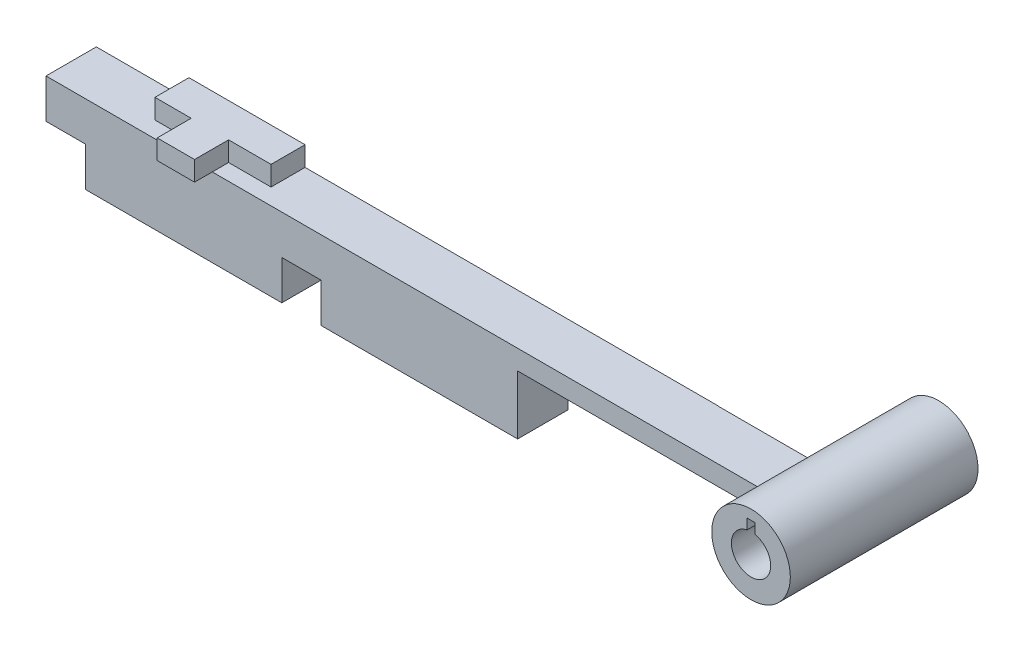
SolidWorks part; units mm, degrees
ref_plane "Front Plane" through (0, 0, 0) normal (0, 0, 1) x (1, 0, 0)
ref_plane "Top Plane" through (0, 0, 0) normal (0, 1, 0) x (1, 0, 0)
ref_plane "Right Plane" through (0, 0, 0) normal (1, 0, 0) x (0, 0, -1)
sketch "Sketch1" plane through (0, 0, 0) normal (0, 1, 0) x (1, 0, 0)
  line L1 (0, 0) -> (14, 0)
  line L2 (0, 0) -> (0, 10)
  line L3 (0, 10) -> (14, 10)
  line L4 (14, 0) -> (14, 10)
extrude "Boss-Extrude1" add sketch "Sketch1" along normal blind 5
sketch "Sketch2" plane through (0, 5, 0) normal (0, 1, 0) x (1, 0, 0)
  line L0 (7, 10) -> (7, 0)
  line L1 (14, 10) -> (0, 10) construction
  line L2 (0, 0) -> (14, 0) construction
  line L3 (7, 5) -> (9, 5)
  line L4 (7, 5) -> (5, 5)
  line L5 (5, 5) -> (5, 5.9618)
  line L6 (5, 5.9618) -> (5, 3.9618)
  line L7 (5, 3.9618) -> (9, 3.9618)
  line L8 (9, 3.9618) -> (9, 5.9618)
  line L9 (9, 5.9618) -> (5, 5.9618)
  line L10 (7, 5.9618) -> (6, 5.9618)
  line L11 (6, 5.9618) -> (6, 7.6627)
  line L12 (6, 7.6627) -> (8.1375, 7.6627)
  line L13 (8.1375, 5.9618) -> (8.1375, 7.6627)
  line L14 (8.1375, 3.9618) -> (8.1375, 1.9618)
  line L15 (8.1375, 1.9618) -> (6, 1.9618)
  line L16 (6, 1.9618) -> (6, 3.9618)
extrude "Boss-Extrude2" add sketch "Sketch2" along normal blind 3 contours L9 L13 L12 L0 | L12 L11 L9 L0 | L0 L9 L5 L4 | L6 L7 L0 L4 | L8 L9 L0 L3 | L7 L8 L3 L0 | L16 L15 L0 L7 | L15 L14 L7 L0
sketch "Sketch3" plane through (0, 0, 0) normal (0, -1, 0) x (1, 0, 0)
  line L1 (0, -10) -> (14, -10)
  line L2 (0, -10) -> (0, 0)
  line L3 (0, 0) -> (14, 0)
  line L4 (14, -10) -> (14, 0)
extrude "Cut-Extrude1" cut sketch "Sketch3" against normal blind 3
sketch "Sketch5" plane through (0, 3, 0) normal (0, -1, 0) x (1, 0, 0)
  line L0 (7, 0) -> (2, 0)
  line L1 (14, 0) -> (0, 0) construction
  line L2 (2, 0) -> (12, 0)
  line L3 (12, 0) -> (12, -3)
  line L4 (12, -3) -> (2, -3)
  line L5 (2, -3) -> (2, 0)
  line M8 (14, 0) -> (0, 0)
extrude "Boss-Extrude3" add sketch "Sketch5" along normal blind 9 contours L5 L4 L3 M8
sketch "Sketch6" plane through (14, 0, 0) normal (1, 0, 0) x (0, 0, -1)
  line L1 (0, 3) -> (10, 3)
  line L2 (0, 3) -> (0, 5)
  line L3 (0, 5) -> (10, 5)
  line L4 (10, 3) -> (10, 5)
extrude "Boss-Extrude4" add sketch "Sketch6" along normal blind 43
sketch "Sketch7" plane through (0, 0, 0) normal (0, 0, 1) x (1, 0, 0)
  line L0 (57, 5) -> (57, 3) construction
  circle A0 centre (57, 4) radius 5
extrude "Boss-Extrude5" add sketch "Sketch7" against normal blind 14 and the other way blind 23
sketch "Sketch8" plane through (0, 3, 0) normal (0, -1, 0) x (-1, 0, 0)
  line L0 (-12, 0) -> (-14, 0)
  line L1 (-52.101, 0) -> (-12, 0) construction
  line L2 (-14, 0) -> (-14, 3)
  line L3 (-14, 3) -> (-24, 3)
  line L4 (-24, 3) -> (-24, 0)
  line L5 (-24, 0) -> (-14, 0)
  line M6 (-52.101, 0) -> (-12, 0)
extrude "Boss-Extrude6" add sketch "Sketch8" along normal blind 9 contours L3 L4 L2 M6
sketch "Sketch9" plane through (0, 5, 0) normal (0, 1, 0) x (1, 0, 0)
  line L0 (9, 4.9618) -> (19, 4.9618)
  line L1 (9, 3.9618) -> (9, 5.9618) construction
  line L2 (19, 4.9618) -> (8.1375, 7.6627)
  line L3 (8.1375, 7.6627) -> (19, 7.6627)
  line L4 (19, 7.6627) -> (21, 7.6627)
  line L5 (19, 7.6627) -> (17.0048, 7.6627)
  line L6 (17.0048, 7.6627) -> (17.0048, 1.6627)
  line L7 (17.0048, 1.6627) -> (21, 1.6627)
  line L8 (21, 1.6627) -> (21, 7.6627)
  line L9 (17.0048, 7.6627) -> (18.0024, 7.6627)
  line L10 (18.0024, 7.6627) -> (18.0024, 1.6627)
  line L11 (18.0024, 1.6627) -> (20, 1.6627)
  line L12 (20, 1.6627) -> (20, 7.6627)
  line L13 (20, 7.6627) -> (20, 4.6627)
  line L14 (20, 4.6627) -> (20, 7.6627)
  line L15 (20, 6.1627) -> (21.5, 6.1627)
  line L16 (21.5, 6.1627) -> (21.5, 3.1627)
  line L17 (21.5, 3.1627) -> (20, 3.1627)
  line L18 (20, 3.1627) -> (15.5, 3.1627)
  line L19 (15.5, 3.1627) -> (15.5, 6.1627)
  line L20 (16, 6.1619) -> (16, 3.1627)
  line L21 (15.5, 6.1627) -> (16, 6.1619)
  line L22 (16, 3.1627) -> (16, 6.1619)
  line L23 (16.1006, 6.1619) -> (17.0048, 6.1619)
  line L24 (16, 6.1619) -> (16.1006, 6.1619)
  line L25 (17.0048, 6.1619) -> (18.0024, 6.1619)
extrude "Boss-Extrude7" add sketch "Sketch9" along normal blind 3 contours L25 L6 L2 L10 | L24 L20 L2 L6 L23 | L2 L20 L0 L6 | L10 L2 L6 L0 | L0 L20 L18 L6 | L18 L10 L0 L6 | L2 L10 L0 | L18 L12 L14 L4 L5 L10 L2 L0 | L17 L8 L15 L12 | L12 L18 L10 L7
sketch "Sketch10" plane through (0, 8, 0) normal (0, 1, 0) x (1, 0, 0)
  line L0 (18.0024, 6.1619) -> (17.0012, 6.1619)
  line L1 (16, 6.1619) -> (18.0024, 6.1619) construction
  line L2 (17.0012, 6.1619) -> (17.0012, 3.1627)
  line L3 (18.0024, 3.1627) -> (16, 3.1627) construction
  line L4 (17.0012, 3.1627) -> (16, 3.1627)
  line L5 (16, 6.1619) -> (16, 3.1627) construction
  line L6 (16, 6.1619) -> (16, 3.1627) construction
  line L7 (16, 3.1627) -> (16, 6.1619)
  line L8 (16, 6.1619) -> (17.0012, 6.1619)
  line M5 (16, 6.1619) -> (16, 3.1627)
  line M6 (16, 3.1627) -> (18.0024, 3.1627)
  line M16 (18.0024, 6.1619) -> (16, 6.1619)
extrude "Cut-Extrude2" cut sketch "Sketch10" against normal blind 3 contours L2 M16 M5 M6
sketch "Sketch11" plane through (0, 0, 23) normal (0, 0, 1) x (1, 0, 0)
  line L0 (52, 4) -> (62, 4)
  line L1 (57, 6) -> (57, 6.7951)
  line L2 (57, 6.7951) -> (57.5, 6.7951)
  line L3 (57.5, 6.7951) -> (57.5, 5.9365)
  line L4 (57, 6.7951) -> (56.5, 6.7951)
  line L5 (56.5, 6.7951) -> (56.5, 5.9365)
  arc A0 (52.101, 5) -> (52.101, 3) centre (57, 4) ccw construction
  circle A1 centre (57, 4) radius 5 construction
  circle A2 centre (57, 4) radius 2
extrude "Cut-Extrude3" cut sketch "Sketch11" against normal blind 43 contours A2 L1 L4 L5 | A2 L3 L2 L1 | L0 A2 | L0 A2
sketch "Sketch12" plane through (0, 8, 0) normal (0, 1, 0) x (1, 0, 0)
  line L1 (6, 1.9618) -> (8.1375, 1.9618)
  line L2 (6, 1.9618) -> (6, 7.6627)
  line L3 (6, 7.6627) -> (8.1375, 7.6627)
  line L4 (8.1375, 1.9618) -> (8.1375, 7.6627)
  line L5 (5, 3.9618) -> (9, 3.9618)
  line L6 (5, 3.9618) -> (5, 5.9618)
  line L7 (5, 5.9618) -> (9, 5.9618)
  line L8 (9, 3.9618) -> (9, 5.9618)
  line L9 (17.0012, 3.1627) -> (21, 3.1627)
  line L10 (17.0012, 3.1627) -> (17.0012, 6.1627)
  line L11 (17.0012, 6.1627) -> (21, 6.1627)
  line L12 (21, 3.1627) -> (21, 6.1627)
  line L13 (18.0024, 1.6627) -> (20, 1.6627)
  line L14 (18.0024, 1.6627) -> (18.0024, 7.6627)
  line L15 (18.0024, 7.6627) -> (20, 7.6627)
  line L16 (20, 1.6627) -> (20, 7.6627)
  line M5 (6, 3.9618) -> (6, 1.9618)
  line M6 (6, 1.9618) -> (8.1375, 1.9618)
  line M7 (8.1375, 1.9618) -> (8.1375, 3.9618)
  line M8 (8.1375, 3.9618) -> (9, 3.9618)
  line M9 (9, 3.9618) -> (9, 5.9618)
  line M10 (9, 5.9618) -> (8.1375, 5.9618)
  line M11 (8.1375, 5.9618) -> (8.1375, 7.6627)
  line M12 (8.1375, 7.6627) -> (6, 7.6627)
  line M13 (6, 7.6627) -> (6, 5.9618)
  line M14 (6, 5.9618) -> (5, 5.9618)
  line M15 (5, 5.9618) -> (5, 3.9618)
  line M16 (5, 3.9618) -> (6, 3.9618)
extrude "Cut-Extrude4" cut sketch "Sketch12" against normal blind 4 contours L5 M5 M6 M7 | L7 L2 L5 L4 | L2 M16 M14 M15 | L7 M13 M11 M12 | L4 M8 M9 M10 | L13 L16 L9 L14 | L9 L16 L11 L14 | L16 L9 L12 L11 | L11 L16 L15 L14 | L9 L14 L11 L10
sketch "Sketch14" plane through (0, 3, 0) normal (0, -1, 0) x (1, 0, 0)
  line L0 (52.101, 0) -> (52.101, -10) construction
  line L1 (0, -10) -> (24, -10)
  line L2 (0, -10) -> (0, -3)
  line L3 (0, -3) -> (24, -3)
  line L4 (24, -10) -> (24, -3)
  line L5 (24, -10) -> (52.101, -10)
  line L6 (24, -10) -> (24, -3)
  line L7 (24, -3) -> (52.101, -3)
  line L8 (52.101, -10) -> (52.101, -3)
  line M2 (24, -3) -> (14, -3)
  line M6 (12, -3) -> (2, -3)
  line M9 (0, 0) -> (0, -10)
  line M10 (0, -10) -> (52.101, -10)
  line M11 (52.101, -10) -> (52.101, 0)
extrude "Cut-Extrude6" cut sketch "Sketch14" against normal blind 4 contours L4 L3 M10 M2 M6 M9 | L7 L4 M10 M11
sketch "Sketch15" plane through (0, 4, 0) normal (0, 1, 0) x (1, 0, 0)
  line L1 (18.0024, 1.6627) -> (20, 1.6627)
  line L2 (18.0024, 1.6627) -> (18.0024, 3)
  line L3 (18.0024, 3) -> (20, 3)
  line L4 (20, 1.6627) -> (20, 3)
  line L5 (6, 1.9618) -> (8.1375, 1.9618)
  line L6 (6, 1.9618) -> (6, 3)
  line L7 (6, 3) -> (8.1375, 3)
  line L8 (8.1375, 1.9618) -> (8.1375, 3)
extrude "Boss-Extrude8" add sketch "Sketch15" along normal blind 1
sketch "Sketch16" plane through (0, 5, 0) normal (0, 1, 0) x (1, 0, 0)
  line L3 (4.7132, 0.8299) -> (10.6225, 0.8299)
  line L4 (4.7132, 0.8299) -> (4.7132, 2.5614)
  line L5 (6.5593, -0.9012) -> (8.4612, -0.9012)
  line L6 (6.5593, -0.9012) -> (6.5593, 4.4069)
  line L7 (6.5593, 4.4069) -> (8.4612, 4.4069)
  line L8 (8.4612, -0.9012) -> (8.4612, 4.4069)
  line L9 (4.7132, 2.5614) -> (10.6225, 2.5614)
  line L10 (10.6225, 0.8299) -> (10.6225, 2.5614)
  line M10 (52.101, 3) -> (0, 3)
  line M12 (0, 0) -> (52.101, 0)
extrude "Boss-Extrude9" add sketch "Sketch16" along normal blind 1 contours L3 L10 L9 L8 | L9 L6 L3 L8 | L8 L7 L6 M10 | L5 L8 L6 M12 | L9 L4 L3 L6 | L8 L3 L6 M12 | L6 L9 L8 M10
sketch "Sketch17" plane through (0, 3, 0) normal (0, -1, 0) x (1, 0, 0)
  line L1 (24, -3) -> (52.101, -3)
  line L2 (24, -3) -> (24, 0)
  line L3 (24, 0) -> (52.101, 0)
  line L4 (52.101, -3) -> (52.101, 0)
extrude "Cut-Extrude7" cut sketch "Sketch17" against normal blind 1
sketch "Sketch18" plane through (0, 0, 23) normal (0, 0, 1) x (1, 0, 0)
  circle A0 centre (57, 4) radius 5
extrude "Cut-Extrude8" cut sketch "Sketch18" against normal blind 7
sketch "Sketch19" plane through (0, 0, -14) normal (0, 0, -1) x (-1, 0, 0)
  circle A0 centre (-57, 4) radius 5
extrude "Cut-Extrude9" cut sketch "Sketch19" against normal blind 8
sketch "Sketch20" plane through (0, 0, 16) normal (0, 0, 1) x (1, 0, 0)
  circle A0 centre (57, 4) radius 5
extrude "Cut-Extrude10" cut sketch "Sketch20" against normal blind 31
sketch "Sketch21" plane through (0, 5, 0) normal (0, 1, 0) x (1, 0, 0)
  line L0 (52.101, 3) -> (8.4612, 3) construction
  line L1 (52.101, 0) -> (34.604, 0)
  line L2 (52.101, 0) -> (52.101, 3)
  line L3 (52.101, 3) -> (34.604, 3)
  line L4 (34.604, 0) -> (34.604, 3)
extrude "Cut-Extrude11" cut sketch "Sketch21" against normal blind 31
sketch "Sketch22" plane through (0, -6, 0) normal (0, -1, 0) x (1, 0, 0)
  line L1 (2, -3) -> (12, -3)
  line L2 (2, -3) -> (2, 0)
  line L3 (2, 0) -> (12, 0)
  line L4 (12, -3) -> (12, 0)
  line L5 (14, -3) -> (24, -3)
  line L6 (14, -3) -> (14, 0)
  line L7 (14, 0) -> (24, 0)
  line L8 (24, -3) -> (24, 0)
extrude "Cut-Extrude12" cut sketch "Sketch22" against normal blind 7
sketch "Sketch23" plane through (0, 6, 0) normal (0, 1, 0) x (1, 0, 0)
  line L1 (6.5593, 4.4069) -> (8.4612, 4.4069)
  line L2 (6.5593, 4.4069) -> (6.5593, 3)
  line L3 (6.5593, 3) -> (8.4612, 3)
  line L4 (8.4612, 4.4069) -> (8.4612, 3)
extrude "Cut-Extrude13" cut sketch "Sketch23" against normal blind 2
sketch "Sketch24" plane through (0, 0, 0) normal (0, 0, 1) x (1, 0, 0)
  line L0 (34.604, 4) -> (34.604, 5) construction
  circle A0 centre (34.604, 4.5) radius 3
extrude "Boss-Extrude10" add sketch "Sketch24" along normal blind 10 and the other way blind 6
sketch "Sketch25" plane through (0, 0, 10) normal (0, 0, 1) x (1, 0, 0)
  line L0 (31.604, 4.5) -> (37.604, 4.5)
  line L1 (34.604, 5.5) -> (34.604, 6)
  line L2 (34.604, 6) -> (34.804, 6)
  line L3 (34.804, 6) -> (34.804, 5.4798)
  line L4 (34.804, 5.4798) -> (34.604, 6)
  line L5 (34.404, 6) -> (34.604, 6)
  line L6 (34.404, 6) -> (34.404, 5.4798)
  arc A0 (31.6459, 5) -> (31.6459, 4) centre (34.604, 4.5) ccw construction
  circle A1 centre (34.604, 4.5) radius 3 construction
  circle A2 centre (34.604, 4.5) radius 1
extrude "Cut-Extrude14" cut sketch "Sketch25" against normal blind 16 contours L0 A2 | L0 A2 | L4 L3 L2 | A2 L4 L1 | A2 L1 L5 L6
sketch "Sketch26" plane through (0, 0, 10) normal (0, 0, 1) x (1, 0, 0)
  circle A0 centre (34.604, 4.5) radius 3
  circle A1 centre (34.604, 4.5) radius 2.5
extrude "Cut-Extrude18" cut sketch "Sketch26" against normal blind 10 contours A1 | A0
sketch "Sketch27" plane through (0, 0, -6) normal (0, 0, -1) x (-1, 0, 0)
  circle A0 centre (-34.604, 4.5) radius 3
  circle A1 centre (-34.604, 4.5) radius 2.5
extrude "Cut-Extrude19" cut sketch "Sketch27" against normal blind 3 contours A0
sketch "Sketch28" plane through (0, 0, 10) normal (0, 0, 1) x (1, 0, 0)
  circle A0 centre (34.604, 4.5) radius 2.5
extrude "Cut-Extrude20" cut sketch "Sketch28" against normal blind 4
sketch "Sketch29" plane through (0, 5, 0) normal (0, 1, 0) x (1, 0, 0)
  line L1 (0, 3) -> (10.6225, 3)
  line L2 (0, 3) -> (0, 2.5614)
  line L3 (0, 2.5614) -> (10.6225, 2.5614)
  line L4 (10.6225, 3) -> (10.6225, 2.5614)
  line L5 (10.6225, 2.5614) -> (31.6459, 2.5614)
  line L6 (10.6225, 2.5614) -> (10.6225, 3)
  line L7 (10.6225, 3) -> (31.6459, 3)
  line L8 (31.6459, 2.5614) -> (31.6459, 3)
  line M5 (4.7132, 2.5614) -> (6.5593, 2.5614)
  line M6 (6.5593, 2.5614) -> (6.5593, 3)
  line M7 (6.5593, 3) -> (0, 3)
  line M8 (0, 3) -> (0, 0)
extrude "Cut-Extrude22" cut sketch "Sketch29" against normal blind 7 and the other way blind 2 contours L3 M8 M5 M6 M7 | L4 L1 L3 M6 | L5 L8 L7 L4
sketch "Sketch30" plane through (0, 0, 6) normal (0, 0, 1) x (1, 0, 0)
  circle A0 centre (34.604, 4.5) radius 3
extrude "Cut-Extrude23" cut sketch "Sketch30" against normal blind 10
sketch "Sketch31" plane through (0, 0, 0) normal (0, 0, 1) x (1, 0, 0)
  line L0 (31.6459, 4) -> (24, 4) construction
  line L1 (28.802, 4) -> (31.2329, 4)
  line L2 (28.802, 4) -> (28.802, 5)
  line L3 (28.802, 5) -> (31.2329, 5)
  line L4 (31.2329, 4) -> (31.2329, 5)
  line L5 (8.4612, 5) -> (31.6459, 5) construction
  line L7 (31.2329, 4) -> (37.4677, 4)
  line L8 (31.2329, 4) -> (31.2329, 5)
  line L9 (31.2329, 5) -> (37.4677, 5)
  line L10 (37.4677, 4) -> (37.4677, 5)
  arc M6 (31.6459, 4) -> (31.6459, 5) centre (34.604, 4.5) cw
extrude "Boss-Extrude11" add sketch "Sketch31" against normal blind 2.55 contours L7 L10 L9 M6
sketch "Sketch32" plane through (0, 0, 0) normal (0, 0, 1) x (1, 0, 0)
  line L0 (24, 4) -> (37.4677, 4)
  line L1 (37.4677, 4) -> (30.7339, 4)
  line L2 (30.7339, 4) -> (34.1008, 4)
  line L3 (34.1008, 4) -> (34.1008, 5)
  line L4 (8.4612, 5) -> (37.4677, 5) construction
  circle A0 centre (34.1008, 4.5) radius 2
  line M3 (37.4677, 5) -> (8.4612, 5)
extrude "Boss-Extrude12" add sketch "Sketch32" along normal blind 7.55 and the other way blind 6 contours A0 M3 | L1 A0 L3 M3 | A0 L2 L3 M3 | L2 A0 L1
sketch "Sketch33" plane through (0, 0, 7.55) normal (0, 0, 1) x (1, 0, 0)
  line L0 (32.1008, 4.5) -> (36.1008, 4.5)
  line L1 (34.1008, 5.5) -> (34.1008, 6)
  line L2 (34.1008, 6) -> (34.3008, 6)
  line L3 (34.3008, 6) -> (34.3008, 5.4798)
  line L4 (34.3008, 5.4798) -> (34.1008, 6)
  line L5 (34.1008, 6) -> (33.9008, 6)
  line L6 (33.9008, 6) -> (33.9008, 5.4798)
  circle A0 centre (34.1008, 4.5) radius 2 construction
  arc A1 (36.0373, 4) -> (36.0373, 5) centre (34.1008, 4.5) ccw construction
  circle A2 centre (34.1008, 4.5) radius 1
extrude "Cut-Extrude24" cut sketch "Sketch33" against normal blind 13.55 contours L0 A2 | L0 A2 | A2 L4 L1 | L4 L3 L2 | A2 L1 L5 L6
sketch "Sketch34" plane through (0, 0, 0) normal (0, 0, 1) x (1, 0, 0)
  line L0 (37.4677, 4) -> (39.9677, 4)
  line L1 (36.0373, 4) -> (37.4677, 4)
  line L2 (36.0373, 4) -> (36.0373, 5)
  line L3 (36.0373, 5) -> (37.4677, 5)
  line L4 (37.4677, 4) -> (37.4677, 5)
  line L5 (37.4677, 5) -> (39.9677, 5)
  line L6 (39.9677, 5) -> (39.9677, 4)
  line L7 (39.017, 5.956) -> (39.9677, 5)
  line L8 (39.9677, 5) -> (41.8177, 6.8398)
  line L9 (41.8177, 6.8398) -> (39.017, 5.956)
  line L10 (40.8927, 7.7698) -> (39.017, 5.956)
  line L11 (40.8927, 7.7698) -> (41.8177, 6.8398)
  arc A1 (37.4677, 4) -> (39.9677, 5) centre (37.3034, 8.0358) ccw
  arc A2 (37.4677, 5) -> (39.017, 5.956) centre (36.0168, 9.0846) ccw
  line M10 (37.4677, 4) -> (37.4677, 5)
extrude "Boss-Extrude13" add sketch "Sketch34" against normal blind 2.55 contours A1 L5 M10 | A2 L5 L7 | L8 L9 L7 | L11 L10 L9
sketch "Sketch35" plane through (0, 0, 0) normal (0, 0, 1) x (1, 0, 0)
  line L0 (40.8927, 7.7698) -> (41.8177, 6.8398) construction
  circle A0 centre (41.3552, 7.3048) radius 2
extrude "Boss-Extrude14" add sketch "Sketch35" along normal blind 6.55 and the other way blind 4
sketch "Sketch36" plane through (0, 0, 7.55) normal (0, 0, 1) x (1, 0, 0)
  circle A0 centre (34.1008, 4.5) radius 2
extrude "Cut-Extrude25" cut sketch "Sketch36" against normal blind 14.55
sketch "Sketch37" plane through (0, 0, 0) normal (0, 0, 1) x (1, 0, 0)
  line L0 (32.1643, 4) -> (24, 4) construction
  line L1 (29.703, 4) -> (31.9259, 4)
  line L2 (29.703, 4) -> (29.703, 5)
  line L3 (29.703, 5) -> (31.9259, 5)
  line L4 (31.9259, 4) -> (31.9259, 5)
  line L5 (8.4612, 5) -> (32.1643, 5) construction
  line L6 (36.0373, 5) -> (37.4677, 5) construction
  line L7 (31.9259, 4) -> (37.2721, 4)
  line L8 (31.9259, 4) -> (31.9259, 5)
  line L9 (31.9259, 5) -> (37.2721, 5)
  line L10 (37.2721, 4) -> (37.2721, 5)
  arc M10 (32.1643, 4) -> (32.1643, 5) centre (34.1008, 4.5) cw
extrude "Boss-Extrude15" add sketch "Sketch37" against normal blind 2.55 contours L7 L10 L9 M10
sketch "Sketch38" plane through (0, 0, 6.55) normal (0, 0, 1) x (1, 0, 0)
  line L0 (41.3552, 8.8048) -> (41.5552, 8.8048)
  line L1 (41.3552, 8.3048) -> (41.3552, 8.8048)
  line L2 (41.5552, 8.8048) -> (41.5552, 8.2846)
  line L3 (41.3552, 8.8048) -> (41.1552, 8.8048)
  line L4 (41.1552, 8.8048) -> (41.1552, 8.2846)
  circle A1 centre (41.3552, 7.3048) radius 1
extrude "Cut-Extrude26" cut sketch "Sketch38" against normal blind 16.55 contours A1 L1 L3 L4 | A1 L2 L0 L1 | A1
sketch "Sketch39" plane through (0, 0, 6.55) normal (0, 0, 1) x (1, 0, 0)
  circle A0 centre (41.3552, 7.3048) radius 2
extrude "Cut-Extrude27" cut sketch "Sketch39" against normal blind 10.55
sketch "Sketch40" plane through (0, 0, 0) normal (0, 0, 1) x (1, 0, 0)
  line L0 (39.5411, 6.4628) -> (40.9553, 7.877)
  line L1 (40.9553, 7.877) -> (40.478, 5.5074)
  line L2 (40.478, 5.5074) -> (41.9014, 6.9309)
  line L3 (41.9014, 6.9309) -> (40.9553, 7.877)
  arc M20 (40.478, 5.5074) -> (39.5411, 6.4628) centre (41.3552, 7.3048) cw
extrude "Boss-Extrude16" add sketch "Sketch40" against normal blind 2.55 contours L1 L0 M20 | L2 L3 L1
sketch "Sketch41" plane through (0, 0, 0) normal (0, 0, 1) x (1, 0, 0)
  line L0 (41.9014, 6.9309) -> (40.9553, 7.877) construction
  circle A0 centre (41.4283, 7.4039) radius 2
extrude "Boss-Extrude17" add sketch "Sketch41" along normal blind 5.55 and the other way blind 4
sketch "Sketch42" plane through (0, 0, 5.55) normal (0, 0, 1) x (1, 0, 0)
  line L0 (41.4283, 8.9039) -> (41.6283, 8.9039)
  line L1 (41.4283, 8.4039) -> (41.4283, 8.9039)
  line L2 (41.6283, 8.9039) -> (41.6283, 8.3837)
  line L3 (41.6283, 8.3837) -> (41.4283, 8.9039)
  line L4 (41.4283, 8.9039) -> (41.2283, 8.9039)
  line L5 (41.2283, 8.9039) -> (41.2283, 8.3837)
  circle A1 centre (41.4283, 7.4039) radius 1
extrude "Cut-Extrude28" cut sketch "Sketch42" against normal blind 13.55 contours A1 | A1 L3 L1 | L3 L2 L0 | A1 L1 L4 L5
